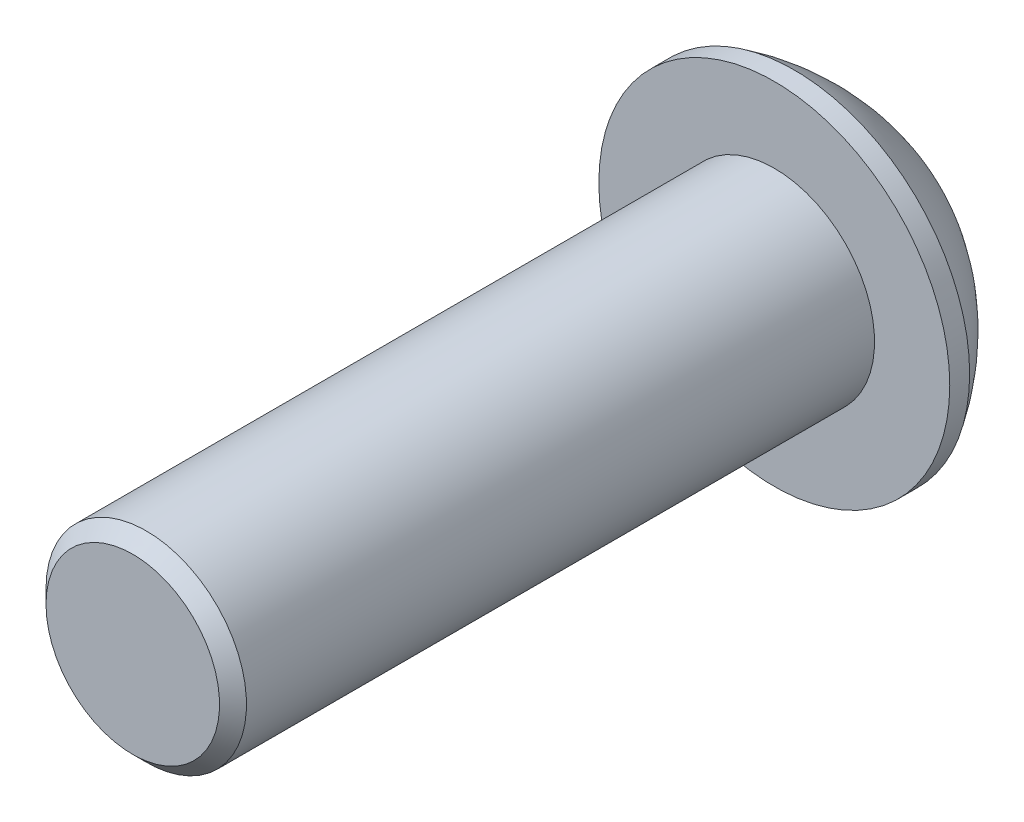
SolidWorks part; units mm, degrees
material "AISI 1020"
ref_plane "Front Plane" through (0, 0, 0) normal (0, 0, 1) x (1, 0, 0)
ref_plane "Top Plane" through (0, 0, 0) normal (0, 1, 0) x (1, 0, 0)
ref_plane "Right Plane" through (0, 0, 0) normal (1, 0, 0) x (0, 0, -1)
sketch "Sketch1" plane through (0, 0, 0) normal (0, 1, 0) x (1, 0, 0)
  line L0 (0, 0) -> (0, -25.4)
  line L1 (0, -25.4) -> (3.9688, -25.4)
  line L2 (3.9688, -25.4) -> (3.9688, 0)
  line L3 (3.9688, 0) -> (6.9469, 0)
  line L4 (6.9469, 0) -> (6.9469, 0.7874)
  line L6 (3.175, 4.2164) -> (0, 4.2164)
  line L7 (0, 0) -> (0, 4.2164)
  arc A0 (6.9469, 0.7874) -> (3.175, 4.2164) centre (-1.1126, -4.289) ccw
  dimension "D6" = 3.175
  dimension "D7" = 9.525
  dimension "D1" = 3.9688
  dimension "D2" = 4.2164
  dimension "D3" = 0.7874
  dimension "D4" = 6.9469
  dimension "D5" = 25.4
revolve "Revolve1" add sketch "Sketch1" angle 360 about L0
sketch "Sketch2" plane through (0, 0, -4.2164) normal (0, 0, -1) x (-1, 0, 0)
  line L1 (2.7496, 0) -> (1.3748, 2.3813)
  line L2 (1.3748, 2.3813) -> (-1.3748, 2.3813)
  line L3 (-1.3748, 2.3813) -> (-2.7496, 0)
  line L4 (-2.7496, 0) -> (-1.3748, -2.3813)
  line L5 (-1.3748, -2.3813) -> (1.3748, -2.3813)
  line L6 (1.3748, -2.3813) -> (2.7496, 0)
  circle A0 centre (0, 0) radius 2.3813 construction
extrude "Cut-Extrude1" cut sketch "Sketch2" against normal blind 3.175
chamfer "Chamfer1" distance 0.5334 angle 45 1 edges at (-3.9687, 0, 25.4)
